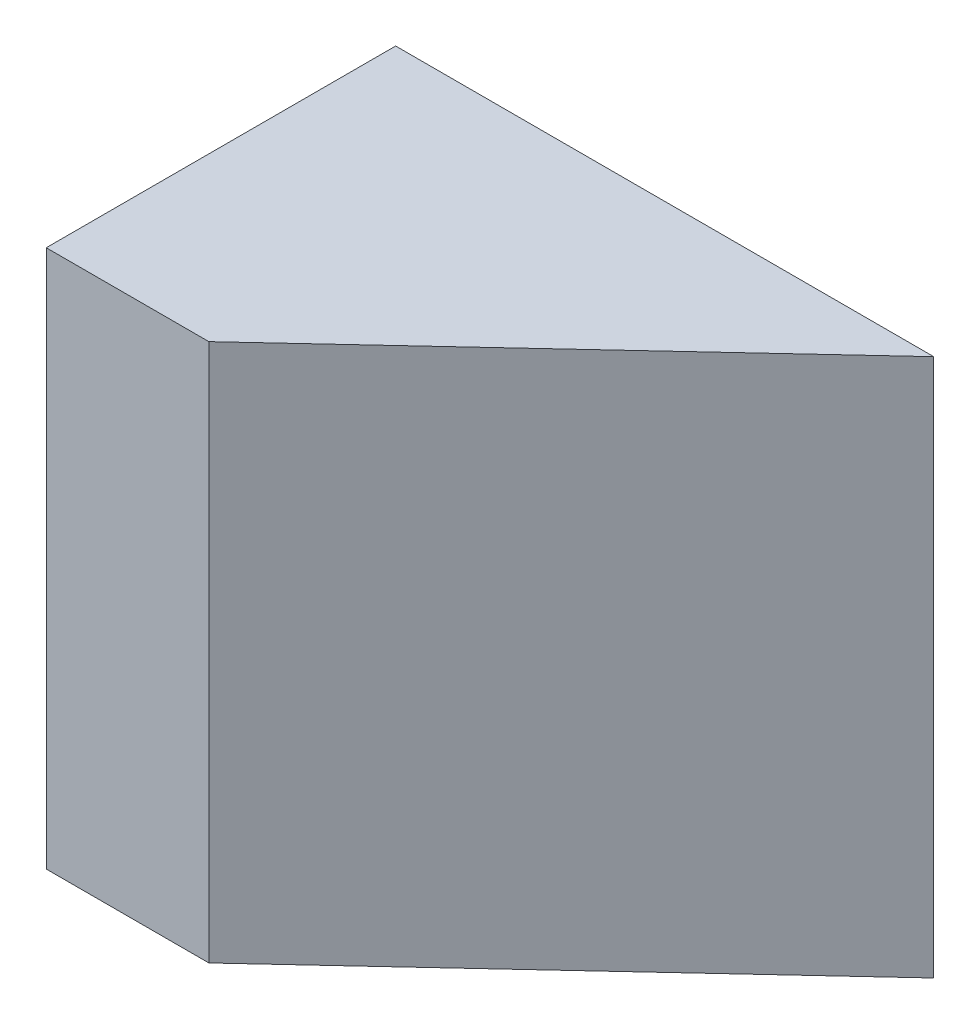
SolidWorks part; units mm, degrees
ref_plane "Plan de face" through (0, 0, 0) normal (0, 0, 1) x (1, 0, 0)
ref_plane "Plan de dessus" through (0, 0, 0) normal (0, 1, 0) x (1, 0, 0)
ref_plane "Plan de droite" through (0, 0, 0) normal (1, 0, 0) x (0, 0, -1)
sketch "Esquisse1" plane through (0, 0, 0) normal (0, 0, 1) x (1, 0, 0)
  line L1 (-77, -77) -> (77, -77)
  line L2 (-77, -77) -> (-77, 77)
  line L3 (-77, 77) -> (77, 77)
  line L4 (77, -77) -> (77, 77)
  point P0 (0, 0)
  dimension "D1" = 154
  dimension "D2" = 154
extrude "Boss.-Extru.1" add sketch "Esquisse1" along normal blind 100
sketch "Esquisse2" plane through (0, -77, 0) normal (0, -1, 0) x (1, 0, 0)
  line L0 (-30.4584, 100) -> (77, 0)
  line L1 (-77, 100) -> (77, 100) construction
  line L3 (-30.4584, 100) -> (77, 100)
  line L4 (77, 100) -> (77, 0)
  dimension "D1" = 146.79
extrude "Enlèv. mat.-Extru.1" cut sketch "Esquisse2" against normal through all
shell "Coque2" thickness 3
